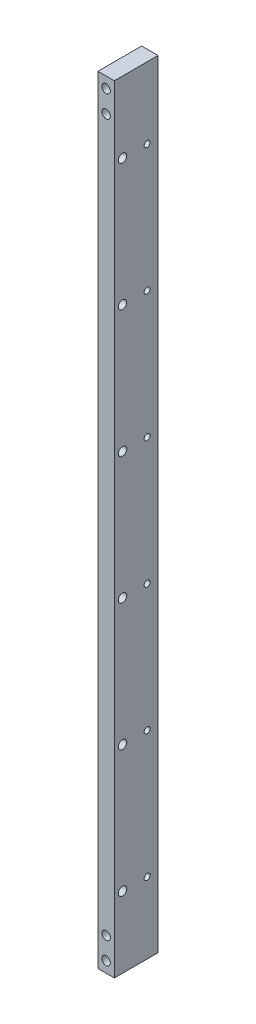
SolidWorks part; units mm, degrees
ref_plane "Front Plane" through (0, 0, 0) normal (0, 0, 1) x (1, 0, 0)
ref_plane "Top Plane" through (0, 0, 0) normal (0, 1, 0) x (1, 0, 0)
ref_plane "Right Plane" through (0, 0, 0) normal (1, 0, 0) x (0, 0, -1)
sketch "Sketch1" plane through (0, 0, 0) normal (0, 1, 0) x (1, 0, 0)
  line L1 (-12.9744, 10.5417) -> (-3.4494, 10.5417)
  line L2 (-12.9744, 10.5417) -> (-12.9744, -14.8583)
  line L3 (-12.9744, -14.8583) -> (-3.4494, -14.8583)
  line L4 (-3.4494, 10.5417) -> (-3.4494, -14.8583)
  dimension "D1" = 9.525
  dimension "D2" = 25.4
extrude "Boss-Extrude1" add sketch "Sketch1" along normal blind 450.85
hole_wizard "CBORE for #8 Socket Head Cap Screw1" positions "Sketch3" profile "Sketch2" counterbore size "#8" standard "ANSI Inch" end condition through all
sketch "Sketch3" plane through (-12.9744, 0, 0) normal (-1, 0, 0) x (0, 0, 1)
  line L0 (14.8583, 450.85) -> (14.8583, 0) construction
  line L1 (-10.5417, 0) -> (14.8583, 0) construction
  point P0 (10.0958, 41.275)
  point P2 (10.0958, 114.935)
  point P4 (10.0958, 188.595)
  point P6 (10.0958, 262.255)
  point P8 (10.0958, 335.915)
  point P10 (10.0958, 409.575)
other "AlignGroup1" parameters "D1"=7.2849, "D2"=0, "D3"=41.275, "D4"=114.935, "D5"=188.595, "D6"=262.255, "D7"=335.915, "D8"=409.575
sketch "Sketch2" plane through (-12.9744, 41.275, 10.0958) normal (0, 1, 0) x (0, 0, 1)
  line L0 (0, 0) -> (0, 9.525)
  line L1 (0, 9.525) -> (2.4574, 9.525)
  line L3 (2.4574, 9.525) -> (2.4574, 5.4356)
  line L4 (2.4574, 5.4356) -> (3.9687, 5.4356)
  line L5 (3.9687, 5.4356) -> (3.9687, 0)
  line L7 (3.9687, 0) -> (0, 0)
  line L11 (0, -6.35) -> (0, 107.95) construction
  dimension "Thru Hole Dia." = 4.9149
  dimension "Thru Hole Depth" = 9.525
  dimension "C'Bore Dia." = 7.9375
  dimension "C'Bore Depth" = 5.4356
hole_wizard "CBORE for #8 Socket Head Cap Screw2" positions "Sketch5" profile "Sketch4" counterbore size "#8" standard "ANSI Inch" end condition through all
sketch "Sketch5" plane through (0, 0, -10.5417) normal (0, 0, -1) x (-1, 0, 0)
  line L0 (3.4494, 450.85) -> (12.9744, 450.85) construction
  line L2 (3.4494, 0) -> (12.9744, 0) construction
  point P0 (8.2119, 6.35)
  point P2 (8.2119, 19.05)
  point P4 (8.2119, 431.8)
  point P6 (8.2119, 444.5)
  point P9 (8.2119, 450.85)
  point P14 (8.2119, 0)
  dimension "D1" = 6.35
  dimension "D2" = 12.7
  dimension "D3" = 6.35
  dimension "D4" = 12.7
sketch "Sketch4" plane through (-8.2119, 6.35, -10.5417) normal (1, 0, 0) x (0, 1, 0)
  line L0 (0, 0) -> (0, 25.4)
  line L1 (0, 25.4) -> (2.4574, 25.4)
  line L3 (2.4574, 25.4) -> (2.4574, 16.8656)
  line L4 (2.4574, 16.8656) -> (3.9687, 16.8656)
  line L5 (3.9687, 16.8656) -> (3.9687, 0)
  line L7 (3.9687, 0) -> (0, 0)
  line L11 (0, -6.35) -> (0, 107.95) construction
  dimension "Thru Hole Dia." = 4.9149
  dimension "Thru Hole Depth" = 25.4
  dimension "C'Bore Dia." = 7.9375
  dimension "C'Bore Depth" = 16.8656
hole_wizard "#8-32 Tapped Hole1" positions "Sketch7" profile "Sketch6" tap size "#8-32" standard "ANSI Inch" end condition through all
sketch "Sketch7" plane through (-12.9744, 0, 0) normal (-1, 0, 0) x (0, 0, 1)
  line L0 (14.8583, 450.85) -> (14.8583, 0) construction
  line L1 (-10.5417, 0) -> (14.8583, 0) construction
  point P0 (-4.1917, 41.275)
  point P2 (-4.1917, 114.935)
  point P4 (-4.1917, 188.595)
  point P6 (-4.1917, 262.255)
  point P8 (-4.1917, 335.915)
  point P10 (-4.1917, 409.575)
other "AlignGroup2" parameters "D1"=469.9, "D2"=19.3415, "D3"=41.275, "D4"=114.935, "D5"=188.595, "D6"=262.255, "D7"=335.915, "D8"=409.575
sketch "Sketch6" plane through (-12.9744, 41.275, -4.1917) normal (0, 1, 0) x (0, 0, 1)
  line L0 (0, 0) -> (0, 9.525)
  line L1 (0, 9.525) -> (1.7272, 9.525)
  line L2 (1.7272, 9.525) -> (1.7272, 0)
  line L5 (1.7272, 0) -> (0, 0)
  line L11 (0, -6.35) -> (0, 107.95) construction
  dimension "Thru Tap Drill Dia." = 3.4544
  dimension "Thru Tap Drill Depth" = 9.525
cosmetic thread "Hole Thread1" parameters "D2"=4.1656
cosmetic thread "Hole Thread2" parameters "D2"=4.1656
cosmetic thread "Hole Thread3" parameters "D2"=4.1656
cosmetic thread "Hole Thread4" parameters "D2"=4.1656
cosmetic thread "Hole Thread5" parameters "D2"=4.1656
cosmetic thread "Hole Thread6" parameters "D2"=4.1656
